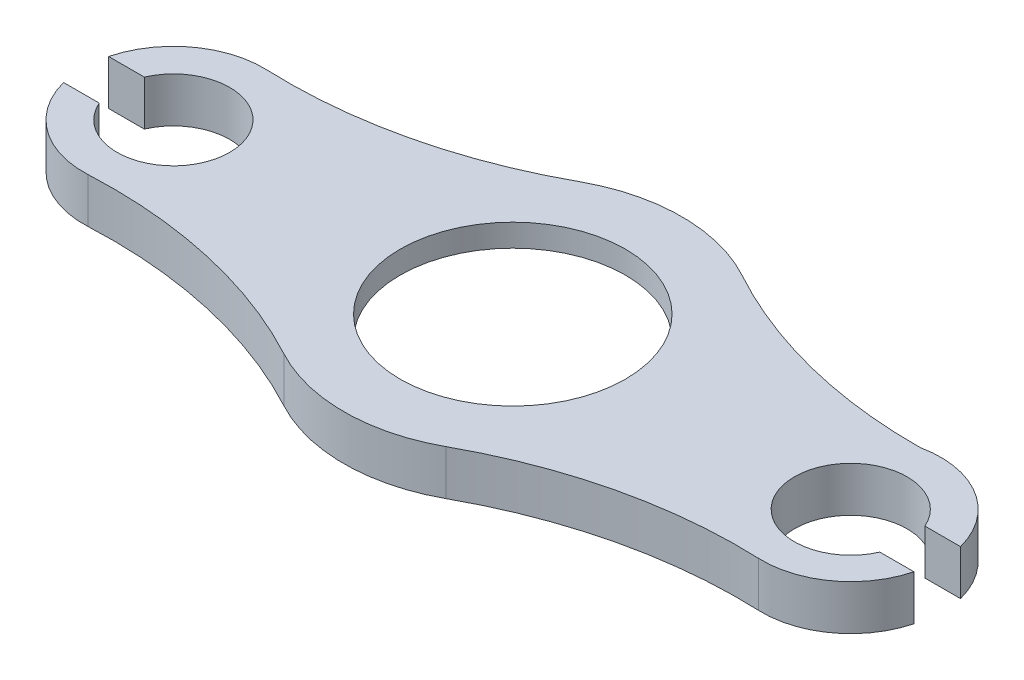
SolidWorks part; units mm, degrees
ref_plane "Front Plane" through (0, 0, 0) normal (0, 0, 1) x (1, 0, 0)
ref_plane "Top Plane" through (0, 0, 0) normal (0, 1, 0) x (1, 0, 0)
ref_plane "Right Plane" through (0, 0, 0) normal (1, 0, 0) x (0, 0, -1)
sketch "Sketch1" plane through (0, 0, 0) normal (0, 1, 0) x (1, 0, 0)
  line L0 (172.9129, 10) -> (188.7298, 10)
  line L1 (-172.9115, 9.3469) -> (-188.7284, 9.3469)
  line L3 (-188.7284, -10.6531) -> (-172.9115, -10.6531)
  line L4 (188.0712, -10) -> (172.9129, -10)
  circle A0 centre (0, 0) radius 50
  arc A2 (-172.9115, -10.6531) -> (-172.9115, 9.3469) centre (-149.9986, -0.6531) ccw
  arc A3 (-188.7284, -10.6531) -> (-148.0227, -40.6042) centre (-149.9986, -0.6531) ccw
  arc A4 (-35.5695, -66.0289) -> (36.1364, -65.7203) centre (0, 0) ccw
  arc A5 (-36.143, 65.7167) -> (-148.3706, 39.3138) centre (-139.6307, 253.882) cw
  arc A6 (-35.5695, -66.0289) -> (-148.0227, -40.6042) centre (-137.4148, -255.0882) ccw
  arc A7 (-148.3706, 39.3138) -> (-188.7284, 9.3469) centre (-149.9986, -0.6531) ccw
  arc A8 (36.143, 65.7167) -> (141.7817, 39.1466) centre (139.6307, 253.882) ccw
  arc A9 (141.7817, 39.1466) -> (188.7298, 10) centre (150, 0) cw
  arc A10 (172.9129, -10) -> (172.9129, 10) centre (150, 0) cw
  arc A11 (188.0712, -10) -> (148.3898, -39.3297) centre (150, 0) cw
  arc A12 (36.1364, -65.7203) -> (148.3898, -39.3297) centre (139.6051, -253.8961) cw
  arc A13 (36.143, 65.7167) -> (-36.143, 65.7167) centre (0, 0) ccw
  point P3 (180.8214, 10)
  point P28 (-180.8199, -10.6531)
  dimension "D1" = 100
  dimension "D3" = 50
  dimension "D4" = 80
  dimension "D7" = 20
  dimension "D9" = 75
  dimension "D6" = 150
  dimension "D8" = 20
extrude "Boss-Extrude1" add sketch "Sketch1" along normal blind 20
sketch "Sketch2" plane through (0, 0, 0) normal (0, 1, 0) x (1, 0, 0)
  circle A0 centre (0, 0) radius 67.8
  circle A1 centre (0, 0) radius 50
  dimension "D1" = 135.6
  dimension "D2" = 100
extrude "Cut-Extrude2" cut sketch "Sketch2" along normal blind 10
